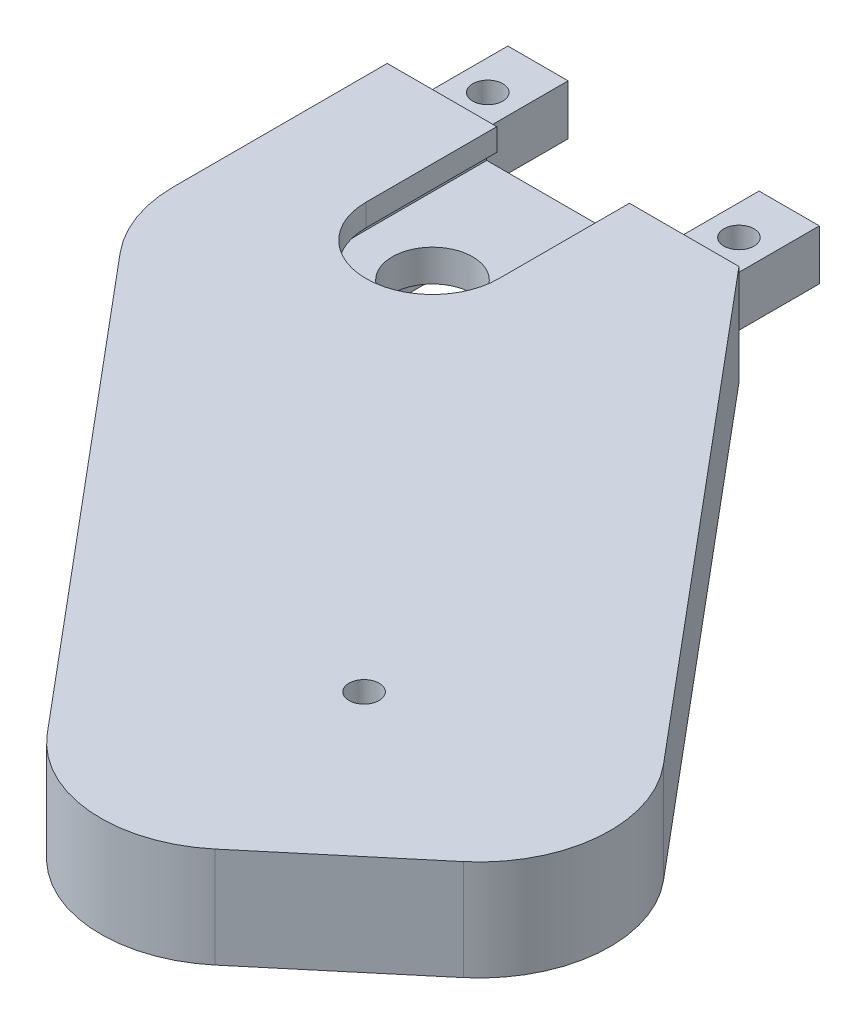
SolidWorks part; units mm, degrees
ref_plane "Front Plane" through (0, 0, 0) normal (0, 0, 1) x (1, 0, 0)
ref_plane "Top Plane" through (0, 0, 0) normal (0, 1, 0) x (1, 0, 0)
ref_plane "Right Plane" through (0, 0, 0) normal (1, 0, 0) x (0, 0, -1)
sketch "Sketch1" plane through (0, 0, 0) normal (0, 1, 0) x (1, 0, 0)
  line L0 (0, 0) -> (6, 0)
  line L1 (6, 0) -> (6, -10)
  line L2 (6, -10) -> (25, -10)
  line L3 (25, -10) -> (25, 0)
  line L4 (25, 0) -> (31, 0)
  line L5 (31, 0) -> (31, -10)
  line L7 (0, -10) -> (0, 0)
  line L8 (0, -10) -> (-2, -10)
  line L11 (33, -36) -> (33, -10)
  line L12 (33, -10) -> (31, -10)
  line L13 (3, 0) -> (3, -5) construction
  line L14 (15.5, -10) -> (15.5, 0) construction
  line L15 (33, -36) -> (-2, -36)
  line L16 (-2, -36) -> (-2, -10)
  circle A0 centre (3, -5) radius 1.5
  circle A1 centre (28, -5) radius 1.5
  dimension "D9" = 3
  dimension "D1" = 36
  dimension "D2" = 35
  dimension "D3" = 10
  dimension "D4" = 6
  dimension "D5" = 2
  dimension "D6" = 6
  dimension "D7" = 2
  dimension "D8" = 5
sketch "Sketch10" plane through (0, 0, 0) normal (0, 1, 0) x (1, 0, 0)
  line L0 (-2, -36) -> (33, -36)
  line L1 (33, -36) -> (33, -10)
  line L2 (33, -10) -> (-2, -10)
  line L3 (-2, -36) -> (-2, -10)
extrude "Boss-Extrude4" add sketch "Sketch10" along normal blind 2.5
extrude "Boss-Extrude5" add sketch "Sketch1" against normal blind 5
sketch "Sketch11" plane through (0, -5, 0) normal (0, -1, 0) x (1, 0, 0)
  line L0 (-2, 36) -> (-2, 10)
  line L1 (-2, 10) -> (33, 10)
  line L2 (33, 10) -> (33, 36)
  line L3 (33, 36) -> (-2, 36)
extrude "Boss-Extrude6" add sketch "Sketch11" along normal blind 2.5
ref_plane "Plane1" through (0, -2.5, 0) normal (0, 1, 0) x (1, 0, 0)
sketch "Sketch3" plane through (0, 0, 10) normal (0, 0, -1) x (-1, 0, 0)
  line L0 (-22.1, 2.5) -> (-22.1, 0.2875)
  line L2 (-22.1, 0.2875) -> (-23.1, 0.2875)
  line L3 (-23.1, 0.2875) -> (-23.1, -0.9125)
  line L4 (-23.1, -0.9125) -> (-15.5, -0.9125)
  line L5 (-15.5, -0.9125) -> (-7.9, -0.9125)
  line L6 (-7.9, -0.9125) -> (-7.9, 0.2875)
  line L7 (-7.9, 0.2875) -> (-8.9, 0.2875)
  line L8 (-8.9, 0.2875) -> (-8.9, 2.5)
  line L9 (-8.9, 2.5) -> (-22.1, 2.5)
  line L10 (-25, -2.5) -> (-6, -2.5) construction
  line L13 (-15.5, -2.5) -> (-15.5, -0.9125) construction
  line L14 (-33, 2.5) -> (2, 2.5) construction
  line L15 (-6, -5) -> (-6, 0) construction
  line L16 (-25, -5) -> (-25, 0) construction
  dimension "D1" = 1.2
  dimension "D2" = 3.4125
  dimension "D3" = 13.2
  dimension "D4" = 15.2
extrude "Cut-Extrude1" cut sketch "Sketch3" against normal blind 13 and the other way through all
sketch "Sketch4" plane through (0, -0.9125, 0) normal (0, 1, 0) x (1, 0, 0)
  line L1 (23.1, -23) -> (7.9, -23) construction
  circle A0 centre (15.5, -23) radius 7.6
  dimension "D1" = 15.2
extrude "Cut-Extrude2" cut sketch "Sketch4" along normal up to surface (1.2 mm away) up to face at (8.4, 0.2875, 16.5)
sketch "Sketch5" plane through (0, -0.9125, 0) normal (0, 1, 0) x (1, 0, 0)
  line L1 (8.9, -23) -> (22.1, -23) construction
  circle A0 centre (15.5, -23) radius 6.6
  dimension "D1" = 13.2
extrude "Cut-Extrude3" cut sketch "Sketch5" along normal through all
sketch "Sketch12" plane through (0, -7.5, 0) normal (0, -1, 0) x (1, 0, 0)
  line L4 (33, 36) -> (-2, 36)
  line L5 (-2, 36) -> (-2, 10)
  line L6 (-2, 10) -> (33, 10)
  line L7 (33, 10) -> (33, 36)
  line L8 (33, 36) -> (-2, 36)
  line L9 (-2, 36) -> (-2, 10)
  line L10 (-2, 10) -> (33, 10)
  line L11 (33, 10) -> (33, 36)
  dimension "D1" = 0
sketch "Sketch8" plane through (0, -0.9125, 0) normal (0, 1, 0) x (1, 0, 0)
  circle A0 centre (15.5, -23) radius 4
  dimension "D1" = 8
extrude "Cut-Extrude6" cut sketch "Sketch8" against normal through all
ref_plane "Plane2" through (0, -2.5, 0) normal (0, 1, 0) x (1, 0, 0)
mirror "Mirror1" about plane through (0, -2.5, 0) normal (0, 1, 0) of "Cut-Extrude3", "Cut-Extrude2", "Cut-Extrude1"
sketch "Sketch13" plane through (0, 2.5, 0) normal (0, 1, 0) x (1, 0, 0)
  line L0 (15.5, -23) -> (73.3509, -91.944) construction
  line L1 (-2, -36) -> (70.6686, -122.603)
  line L2 (33, -10) -> (33, -36) construction
  line L3 (15.5, -23) -> (33, -23) construction
  line L9 (33, -23) -> (33, -10) construction
  line L10 (73.3509, -91.944) -> (87.3392, -108.6147) construction
  line L11 (15.5, -23) -> (15.5, -36) construction
  line L12 (15.5, -36) -> (-2, -36) construction
  line L13 (33, -10) -> (104.0099, -94.6263)
  line L14 (104.0099, -94.6263) -> (70.6686, -122.603)
  line L15 (73.3509, -91.944) -> (90.0216, -77.9556) construction
  line L16 (73.3509, -91.944) -> (56.6802, -105.9324) construction
  line L17 (-2, -36) -> (33, -36)
  line L18 (33, -36) -> (33, -10)
  line L19 (34.3343, -79.3015) -> (51.005, -65.3132) construction
  line L20 (51.005, -65.3132) -> (67.6756, -51.3248) construction
  circle A1 centre (51.005, -65.3132) radius 1.5
  circle A2 centre (28, -5) radius 1.5 construction
  dimension "D1" = 90
  dimension "D2" = 140
extrude "Boss-Extrude7" add sketch "Sketch13" against normal up to surface (10 mm away) up to face at (15.5, -7.5, 20.575)
fillet "Fillet1" radius 13 3 edges at (104.0099, -2.5, 94.6263) (70.6686, -2.5, 122.603) (-2, -2.5, 36)
ref_plane "Plane3" [suppressed] through (-2.2295, 0, 1.8708) normal (-0.766, 0, 0.6428) x (0.6428, 0, 0.766)
ref_plane "Plane4" [suppressed] through (0, -2.5, 0) normal (0, -1, 0) x (-1, 0, 0)
sketch "Sketch14" plane through (-18.9002, 0, 15.8591) normal (-0.766, 0, 0.6428) x (0.6428, 0, 0.766)
  line L0 (117.5822, 2.5) -> (124.1822, 2.5)
  line L1 (28.8724, 2.5) -> (139.3442, 2.5) construction
  line L2 (124.1822, 2.5) -> (124.1822, 0.1875)
  line L3 (124.1822, 0.1875) -> (125.1822, 0.1875)
  line L4 (125.1822, 0.1875) -> (125.1822, -0.9125)
  line L5 (125.1822, -0.9125) -> (117.5822, -0.9125)
  line L6 (117.5822, -0.9125) -> (109.9822, -0.9125)
  line L7 (109.9822, -0.9125) -> (109.9822, 0.1875)
  line L8 (109.9822, 0.1875) -> (110.9822, 0.1875)
  line L9 (110.9822, 0.1875) -> (110.9822, 2.5)
  line L10 (110.9822, 2.5) -> (117.5822, 2.5)
  dimension "D1" = 13.2
  dimension "D2" = 15.2
  dimension "D3" = 3.4125
  dimension "D4" = 1.1
extrude "Cut-Extrude7" [suppressed] cut sketch "Sketch14" against normal up to surface (21.762 mm away)
sketch "Sketch15" [suppressed] plane through (0, 0.1875, 0) normal (0, -1, 0) x (1, 0, 0)
  circle A0 centre (73.3509, 91.944) radius 7.6
  dimension "D1" = 15.2
extrude "Cut-Extrude8" [suppressed] cut sketch "Sketch15" along normal up to surface (1.1 mm away)
sketch "Sketch16" [suppressed] plane through (0, 0.1875, 0) normal (0, -1, 0) x (1, 0, 0)
  circle A0 centre (73.3509, 91.944) radius 6.6
  dimension "D1" = 13.2
extrude "Cut-Extrude9" [suppressed] cut sketch "Sketch16" against normal through all
mirror "Mirror2" [suppressed] about plane through (0, -2.5, 0) normal (0, -1, 0)
sketch "Sketch17" [suppressed] plane through (0, -0.9125, 0) normal (0, 1, 0) x (1, 0, 0)
  circle A0 centre (73.3509, -91.944) radius 4
  dimension "D1" = 8
extrude "Cut-Extrude10" [suppressed] cut sketch "Sketch17" against normal through all contours A0
sketch "Sketch18" plane through (0, 2.5, 0) normal (0, 1, 0) x (1, 0, 0)
  line L0 (47.19, -94.6224) -> (80.5314, -66.6457)
  line L1 (51.005, -65.3132) -> (63.8607, -80.634) construction
  line L8 (80.6271, -114.2468) -> (94.0513, -102.9826)
  line L9 (95.6537, -84.6677) -> (33, -10)
  line L10 (33, -10) -> (22.1, -10)
  line L11 (22.1, -10) -> (22.1, -23)
  line L12 (8.9, -23) -> (8.9, -10)
  line L13 (8.9, -10) -> (-2, -10)
  line L14 (-2, -10) -> (-2, -31.2684)
  line L15 (1.0414, -39.6246) -> (62.3123, -112.6444)
  line L16 (80.6271, -114.2468) -> (94.0513, -102.9826)
  line L17 (95.6537, -84.6677) -> (80.5314, -66.6457)
  line L23 (47.19, -94.6224) -> (62.3123, -112.6444)
  arc A4 (94.0513, -102.9826) -> (95.6537, -84.6677) centre (85.6951, -93.024) ccw
  arc A5 (8.9, -23) -> (22.1, -23) centre (15.5, -23) ccw
  arc A6 (-2, -31.2684) -> (1.0414, -39.6246) centre (11, -31.2684) ccw
  arc A7 (62.3123, -112.6444) -> (80.6271, -114.2468) centre (72.2709, -104.2882) ccw
  arc A8 (94.0513, -102.9826) -> (95.6537, -84.6677) centre (85.6951, -93.024) ccw
  arc A11 (62.3123, -112.6444) -> (80.6271, -114.2468) centre (72.2709, -104.2882) ccw
  dimension "D2" = 20
  dimension "D1" = 0
extrude "Cut-Extrude11" cut sketch "Sketch18" against normal through all
fillet "Fillet2" radius 13 2 edges at (80.5314, -2.5, 66.6457) (47.19, -2.5, 94.6224)
